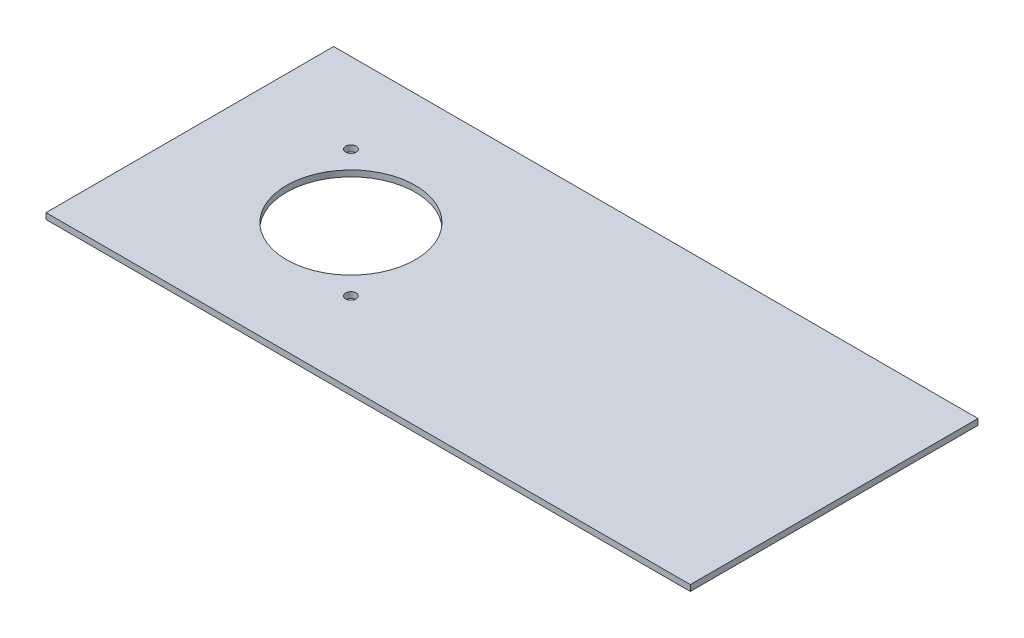
SolidWorks part; units mm, degrees
ref_plane "Front Plane" through (0, 0, 0) normal (0, 0, 1) x (1, 0, 0)
ref_plane "Top Plane" through (0, 0, 0) normal (0, 1, 0) x (1, 0, 0)
ref_plane "Right Plane" through (0, 0, 0) normal (1, 0, 0) x (0, 0, -1)
sketch "Sketch1" plane through (0, 0, 0) normal (0, 1, 0) x (1, 0, 0)
  line L0 (-53.75, 0) -> (-74.9632, 21.2132) construction
  line L1 (107.5, -48) -> (-107.5, -48)
  line L2 (107.5, -48) -> (107.5, 48)
  line L3 (107.5, 48) -> (-107.5, 48)
  line L4 (-107.5, -48) -> (-107.5, 48)
  line L5 (107.5, -48) -> (-107.5, 48) construction
  line L6 (107.5, 48) -> (-107.5, -48) construction
  line L7 (-53.75, 0) -> (-32.5368, -21.2132) construction
  line L8 (-53.75, 0) -> (-73.75, 0) construction
  line L9 (-107.5, 0) -> (0, 0) construction
  circle A0 centre (-53.75, 0) radius 20 construction
  circle A1 centre (-74.9632, 21.2132) radius 1.75
  circle A2 centre (-32.5368, -21.2132) radius 1.75
  circle A3 centre (-53.75, 0) radius 21.5
  point P0 (0, 0)
  point P12 (-54, 0)
  dimension "D1" = 40
  dimension "D3" = 3.5
  dimension "D5" = 43
  dimension "D2" = 30
  dimension "D4" = 45
  dimension "D6" = 215
  dimension "D7" = 96
extrude "Boss-Extrude1" add sketch "Sketch1" along normal blind 2
